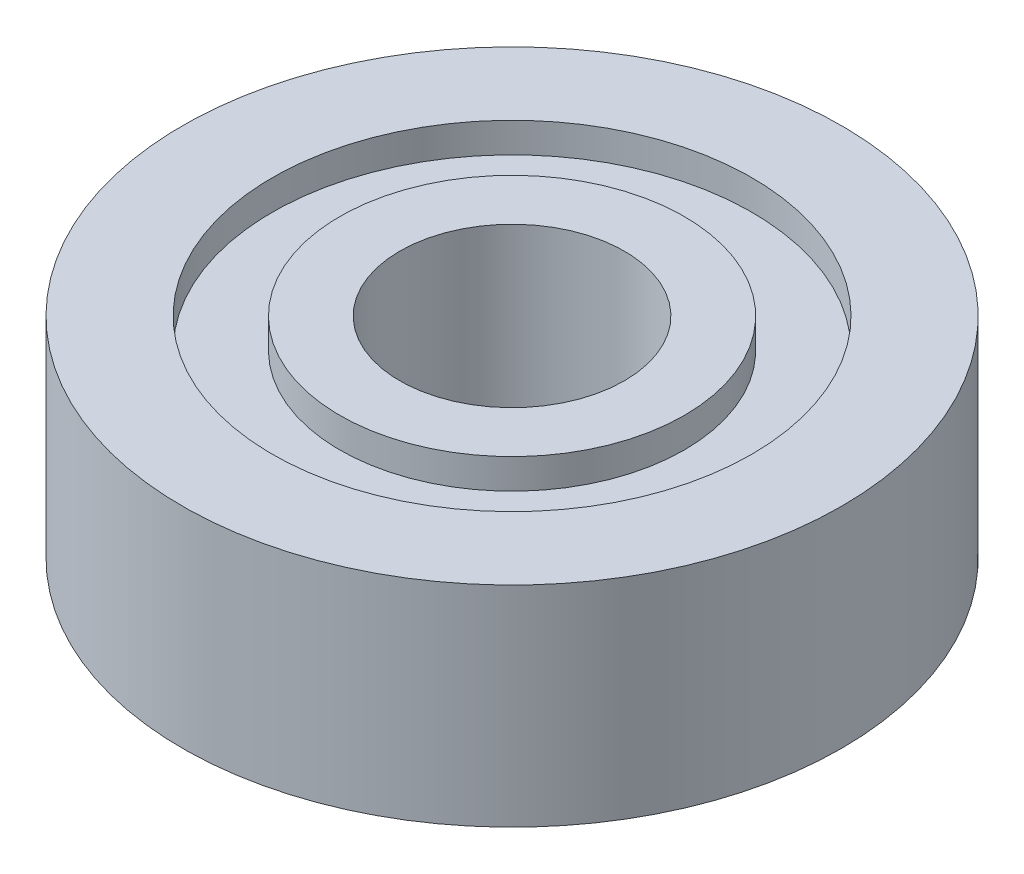
SolidWorks part; units mm, degrees
material "1060 Alloy"
ref_plane "Спереди" through (0, 0, 0) normal (0, 0, 1) x (1, 0, 0)
ref_plane "Сверху" through (0, 0, 0) normal (0, 1, 0) x (1, 0, 0)
ref_plane "Справа" through (0, 0, 0) normal (1, 0, 0) x (0, 0, -1)
sketch "Sketch2" plane through (0, 0, 0) normal (0, 0, 1) x (1, 0, 0)
  line L0 (0, 0) -> (0, 7) construction
  line L1 (0, 7) -> (-3.75, 7) construction
  line L2 (-3.75, 7) -> (-3.75, 0)
  line L3 (-3.75, 0) -> (0, 0) construction
  line L4 (-3.75, 7) -> (-5.75, 7)
  line L5 (-5.75, 7) -> (-5.75, 6)
  line L6 (-5.75, 6) -> (-8, 6)
  line L7 (-8, 6) -> (-8, 7)
  line L8 (-8, 7) -> (-11, 7)
  line L9 (-11, 7) -> (-11, 0)
  line L10 (-11, 0) -> (-8, 0)
  line L11 (-8, 0) -> (-8, 1)
  line L12 (-8, 1) -> (-5.75, 1)
  line L13 (-5.75, 1) -> (-5.75, 0)
  line L14 (-5.75, 0) -> (-3.75, 0)
  dimension "D1" = 3.75
  dimension "D2" = 11
  dimension "D3" = 1
  dimension "D4" = 3
  dimension "D5" = 2
  dimension "D6" = 7
revolve "Revolve1" add sketch "Sketch2" angle 360 about L0
